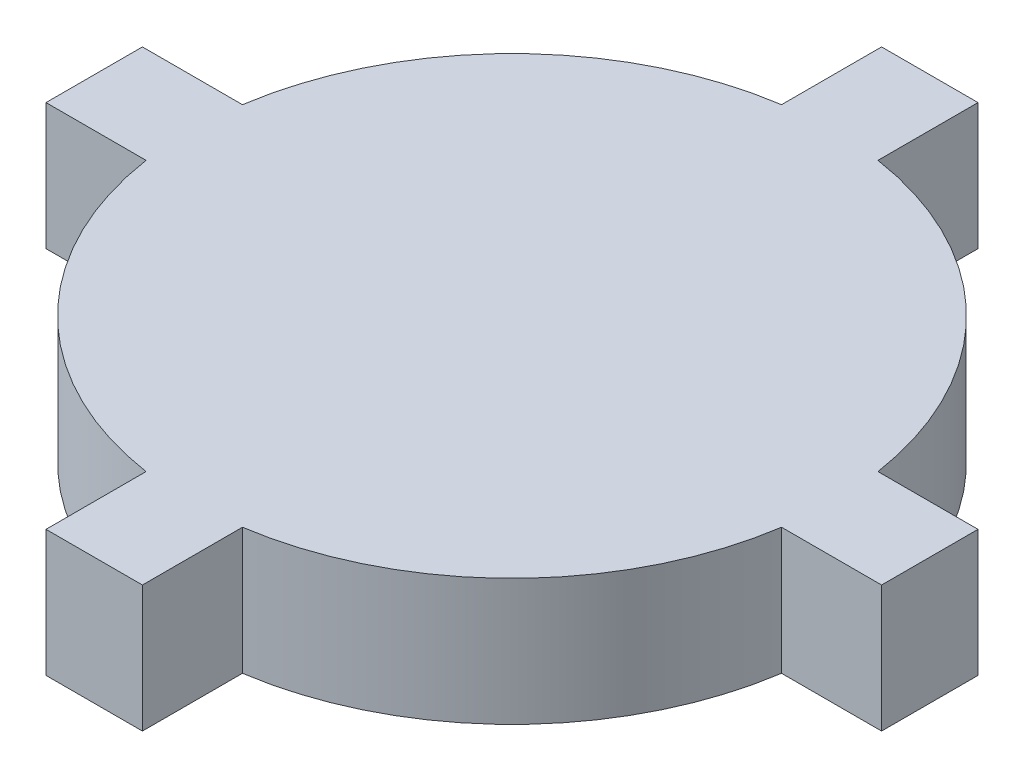
SolidWorks part; units mm, degrees
ref_plane "Front Plane" through (0, 0, 0) normal (0, 0, 1) x (1, 0, 0)
ref_plane "Top Plane" through (0, 0, 0) normal (0, 1, 0) x (1, 0, 0)
ref_plane "Right Plane" through (0, 0, 0) normal (1, 0, 0) x (0, 0, -1)
sketch "Sketch1" plane through (0, 0, 0) normal (0, 1, 0) x (1, 0, 0)
  line L1 (16.51, -1.905) -> (16.51, 1.905)
  line L2 (16.51, 1.905) -> (12.5563, 1.905)
  line L4 (16.51, -1.905) -> (12.5563, -1.905)
  line L5 (16.51, 0) -> (0, 0) construction
  line L6 (1.905, -16.51) -> (1.905, -12.5563)
  line L7 (-1.905, -16.51) -> (1.905, -16.51)
  line L8 (-1.905, -16.51) -> (-1.905, -12.5563)
  line L9 (0, -16.51) -> (0, 0) construction
  line L10 (-16.51, -1.905) -> (-12.5563, -1.905)
  line L11 (-16.51, 1.905) -> (-16.51, -1.905)
  line L12 (-16.51, 1.905) -> (-12.5563, 1.905)
  line L13 (-16.51, 0) -> (0, 0) construction
  line L14 (-1.905, 16.51) -> (-1.905, 12.5563)
  line L15 (1.905, 16.51) -> (-1.905, 16.51)
  line L16 (1.905, 16.51) -> (1.905, 12.5563)
  line L17 (0, 16.51) -> (0, 0) construction
  arc A0 (12.5563, 1.905) -> (1.905, 12.5563) centre (0, 0) ccw
  arc A1 (-12.5563, -1.905) -> (-1.905, -12.5563) centre (0, 0) ccw
  arc A2 (1.905, -12.5563) -> (12.5563, -1.905) centre (0, 0) ccw
  arc A3 (-1.905, 12.5563) -> (-12.5563, 1.905) centre (0, 0) ccw
  point P25 (0, 0)
  dimension "D1" = 25.4
  dimension "D2" = 16.51
  dimension "D3" = 3.81
  dimension "D4" = 4
extrude "Boss-Extrude1" add sketch "Sketch1" along normal blind 5
